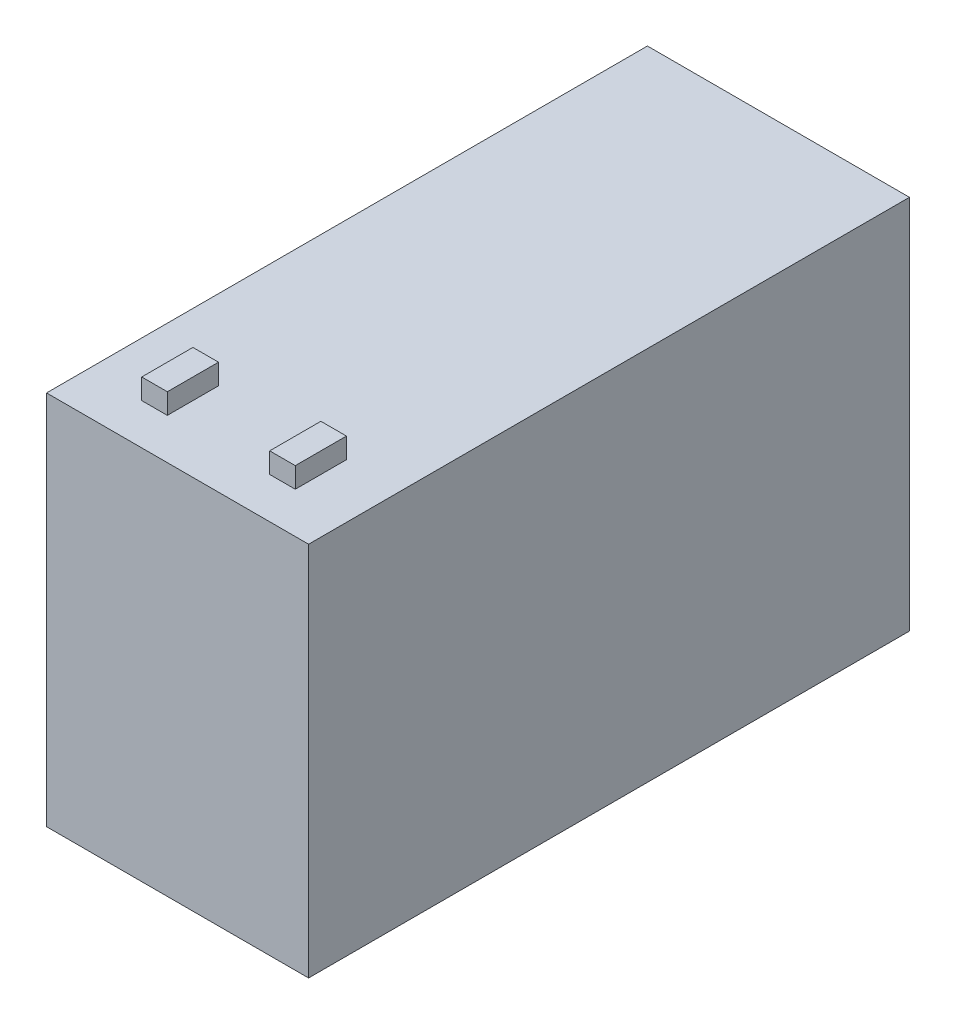
SolidWorks part; units mm, degrees
ref_plane "Front Plane" through (0, 0, 0) normal (0, 0, 1) x (1, 0, 0)
ref_plane "Top Plane" through (0, 0, 0) normal (0, 1, 0) x (1, 0, 0)
ref_plane "Right Plane" through (0, 0, 0) normal (1, 0, 0) x (0, 0, -1)
sketch "Sketch1" plane through (0, 0, 0) normal (0, 0, 1) x (1, 0, 0)
  line L1 (0, 0) -> (65.024, 0)
  line L2 (0, 0) -> (0, 93.218)
  line L3 (0, 93.218) -> (65.024, 93.218)
  line L4 (65.024, 0) -> (65.024, 93.218)
  dimension "D1" = 65.024
  dimension "D2" = 93.218
extrude "Boss-Extrude1" add sketch "Sketch1" along normal blind 149.098
sketch "Sketch2" plane through (0, 93.218, 0) normal (0, 1, 0) x (1, 0, 0)
  line L0 (32.512, -149.098) -> (32.512, 0) construction
  line L1 (65.024, -149.098) -> (0, -149.098) construction
  line L2 (65.024, 0) -> (0, 0) construction
  line L3 (19.812, -138.938) -> (19.812, -126.238)
  line L4 (51.562, -138.938) -> (45.212, -138.938)
  line L5 (51.562, -138.938) -> (51.562, -126.238)
  line L6 (51.562, -126.238) -> (45.212, -126.238)
  line L7 (45.212, -138.938) -> (45.212, -126.238)
  line L8 (13.462, -126.238) -> (19.812, -126.238)
  line L9 (13.462, -138.938) -> (13.462, -126.238)
  line L10 (13.462, -138.938) -> (19.812, -138.938)
  dimension "D1" = 6.35
  dimension "D2" = 12.7
  dimension "D3" = 25.4
  dimension "D4" = 10.16
extrude "Boss-Extrude2" add sketch "Sketch2" along normal blind 5.08
